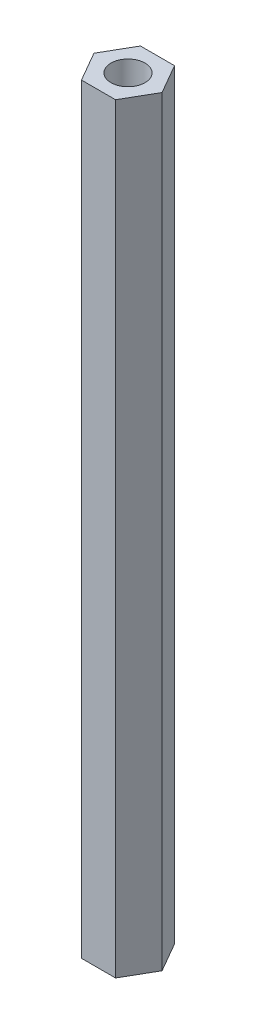
SolidWorks part; units mm, degrees
ref_plane "前视基准面" through (0, 0, 0) normal (0, 0, 1) x (1, 0, 0)
ref_plane "上视基准面" through (0, 0, 0) normal (0, 1, 0) x (1, 0, 0)
ref_plane "右视基准面" through (0, 0, 0) normal (1, 0, 0) x (0, 0, -1)
other "Configuration Table"
sketch "草图1" plane through (0, 0, 0) normal (0, 1, 0) x (1, 0, 0)
  line L1 (3, 0) -> (1.5, 2.5981)
  line L2 (1.5, 2.5981) -> (-1.5, 2.5981)
  line L3 (-1.5, 2.5981) -> (-3, 0)
  line L4 (-3, 0) -> (-1.5, -2.5981)
  line L5 (-1.5, -2.5981) -> (1.5, -2.5981)
  line L6 (1.5, -2.5981) -> (3, 0)
  circle A0 centre (0, 0) radius 2.5981 construction
  circle A1 centre (0, 0) radius 1.5
  dimension "D2" = 3
  dimension "D1" = 3
extrude "凸台-拉伸1" add sketch "草图1" along normal blind 67
